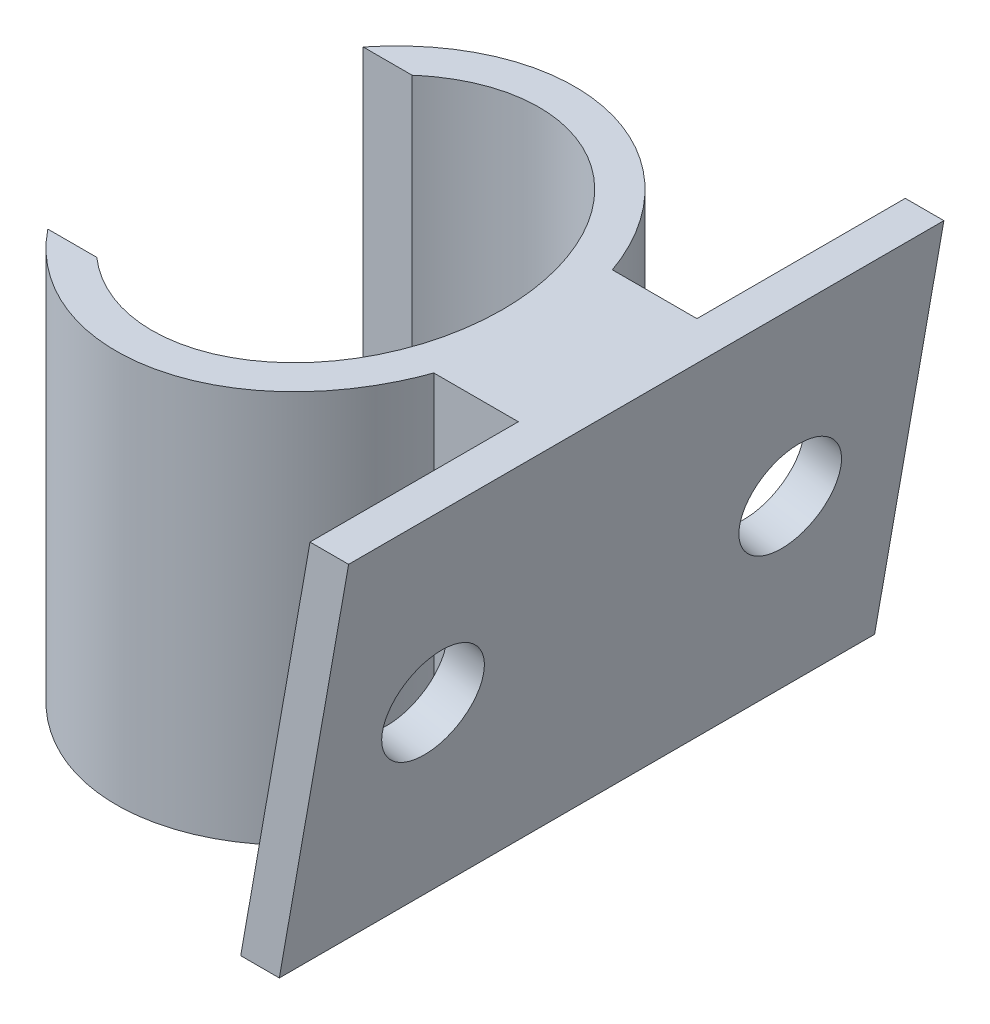
SolidWorks part; units mm, degrees
ref_plane "Alzado" through (0, 0, 0) normal (0, 0, 1) x (1, 0, 0)
ref_plane "Planta" through (0, 0, 0) normal (0, 1, 0) x (1, 0, 0)
ref_plane "Vista lateral" through (0, 0, 0) normal (1, 0, 0) x (0, 0, -1)
sketch "Croquis1" plane through (0, 0, 0) normal (0, 1, 0) x (1, 0, 0)
  line L0 (0, 16.25) -> (0, -16.25) construction
  line L1 (0, 0) -> (-13.2, 0) construction
  line L2 (0, 0) -> (13.2, 0) construction
  line L3 (0, -16.25) -> (0, -19.25) construction
  line L4 (13.2, 0) -> (16.2, 0) construction
  ellipse E0 centre (0, 0) end of major axis (0, -16.25) minor radius 13.2
  ellipse E1 centre (0, 0) end of major axis (0, -19.25) minor radius 16.2
  dimension "D1" = 16.25
  dimension "D2" = 16.25
extrude "Saliente-Extruir1" add sketch "Croquis1" along normal blind 33
sketch "Croquis2" plane through (0, 33, 0) normal (0, 1, 0) x (1, 0, 0)
  line L0 (0, 0) -> (-7.6472, 13.2453)
  line L1 (-7.6472, 13.2453) -> (-17.6691, 13.2453)
  line L2 (-17.6691, 13.2453) -> (-24.7285, -10.2975)
  line L3 (0, 0) -> (-7.6472, -13.2453)
  line L4 (-7.6472, -13.2453) -> (-13.4674, -13.2453)
  line L5 (-13.4674, -13.2453) -> (-24.7285, -10.2975)
  line L6 (0, 0) -> (-7.8151, 0) construction
  ellipse E0 centre (0, 0) end of major axis (0, -16.25) minor radius 13.2 construction
  dimension "D1" = 60
  dimension "D2" = 60
  dimension "D3" = 0
extrude "Cortar-Extruir1" cut sketch "Croquis2" against normal blind 33
sketch "Croquis3" plane through (0, 0, 0) normal (0, 0, 1) x (1, 0, 0)
  line L0 (16.2, 0) -> (22.0188, 33)
  line L1 (22.0188, 33) -> (16.2, 33)
  line L2 (13.2, 33) -> (-7.6472, 33) construction
  line L3 (16.2, 0) -> (16.2, 33) construction
  line L4 (16.2, 33) -> (16.2, 0)
  dimension "D1" = 180
  dimension "D2" = 10
extrude "Saliente-Extruir2" add sketch "Croquis3" along normal blind 30 and the other way blind 30 separate body
sketch "Croquis4" plane through (0, 33, 0) normal (0, 1, 0) x (1, 0, 0)
  line L0 (22.0188, 30) -> (22.0188, -30) construction
  line L1 (16.2, 30) -> (22.0188, 30)
  line L2 (16.2, 30) -> (16.2, 25)
  line L3 (16.2, 25) -> (22.0188, 25)
  line L4 (22.0188, 30) -> (22.0188, 25)
  line L6 (16.2, -30) -> (22.0188, -30)
  line L7 (16.2, -30) -> (16.2, -25)
  line L8 (16.2, -25) -> (22.0188, -25)
  line L9 (22.0188, -30) -> (22.0188, -25)
extrude "Cortar-Extruir2" cut sketch "Croquis4" against normal blind 36
sketch "Croquis5" plane through (0, 33, 0) normal (0, 1, 0) x (1, 0, 0)
  line L0 (17.8185, 0) -> (17.8185, 7.5)
  line L1 (17.8185, 7.5) -> (13.6263, 7.5)
  line L2 (13.6263, 7.5) -> (13.6263, -7.5)
  line L3 (13.6263, -7.5) -> (17.8185, -7.5)
  line L4 (17.8185, -7.5) -> (17.8185, 0)
extrude "Saliente-Extruir4" add sketch "Croquis5" against normal blind 33
sketch "Croquis6" plane through (0, 0, -25) normal (0, 0, -1) x (-1, 0, 0)
  line L0 (-22.0188, 33) -> (-16.2, 0)
  line L1 (-16.2, 0) -> (-19.3455, -0.5546)
  line L2 (-19.3455, -0.5546) -> (-25.0729, 31.9269)
  line L3 (-25.0729, 31.9269) -> (-25.2621, 33)
  line L4 (-25.2621, 33) -> (-22.0188, 33)
  dimension "D1" = 180
extrude "Saliente-Extruir5" add sketch "Croquis6" against normal blind 50
sketch "Croquis7" plane through (0, 0, 25) normal (0, 0, 1) x (1, 0, 0)
  line L0 (16.2, 0) -> (19.4433, 0)
  line L1 (25.2621, 33) -> (19.3455, -0.5546) construction
  line L2 (19.4433, 0) -> (19.3455, -0.5546)
  line L3 (19.3455, -0.5546) -> (16.2, 0)
extrude "Cortar-Extruir3" cut sketch "Croquis7" against normal blind 50
sketch "Croquis8" plane through (0, 0, 25) normal (0, 0, 1) x (1, 0, 0)
  line L0 (16.2, 0) -> (22.0188, 33)
  line L1 (25.2621, 33) -> (16.2, 33) construction
  line L2 (22.0188, 33) -> (16.2, 33)
  line L3 (16.2, 33) -> (16.2, 0)
  line L4 (25.2621, 33) -> (19.4433, 0) construction
  dimension "D1" = 0
extrude "Cortar-Extruir4" cut sketch "Croquis8" against normal up to vertex
sketch "Croquis9" plane through (0, 0, -25) normal (0, 0, -1) x (-1, 0, 0)
  line L0 (-16.2, 0) -> (-22.0188, 33)
  line L1 (-16.2, 33) -> (-25.2621, 33) construction
  line L2 (-22.0188, 33) -> (-16.2, 33)
  line L3 (-16.2, 33) -> (-16.2, 0)
  line L4 (-25.2621, 33) -> (-19.4433, 0) construction
  dimension "D1" = 0
extrude "Cortar-Extruir5" cut sketch "Croquis9" against normal up to vertex
sketch "Croquis11" plane through (18.857, -3.325, 0) normal (0.9848, -0.1736, 0) x (0, 0, -1)
  line L0 (-25, 36.8854) -> (25, 36.8854) construction
  circle A0 centre (-15, 20.1304) radius 4.25
  circle A1 centre (15, 20.1304) radius 4.25
  point P6 (0, 36.8854)
  dimension "D1" = 15
  dimension "D2" = 15
  dimension "D3" = 16.755
  dimension "D4" = 16.755
extrude "Cortar-Extruir6" cut sketch "Croquis11" against normal blind 4
